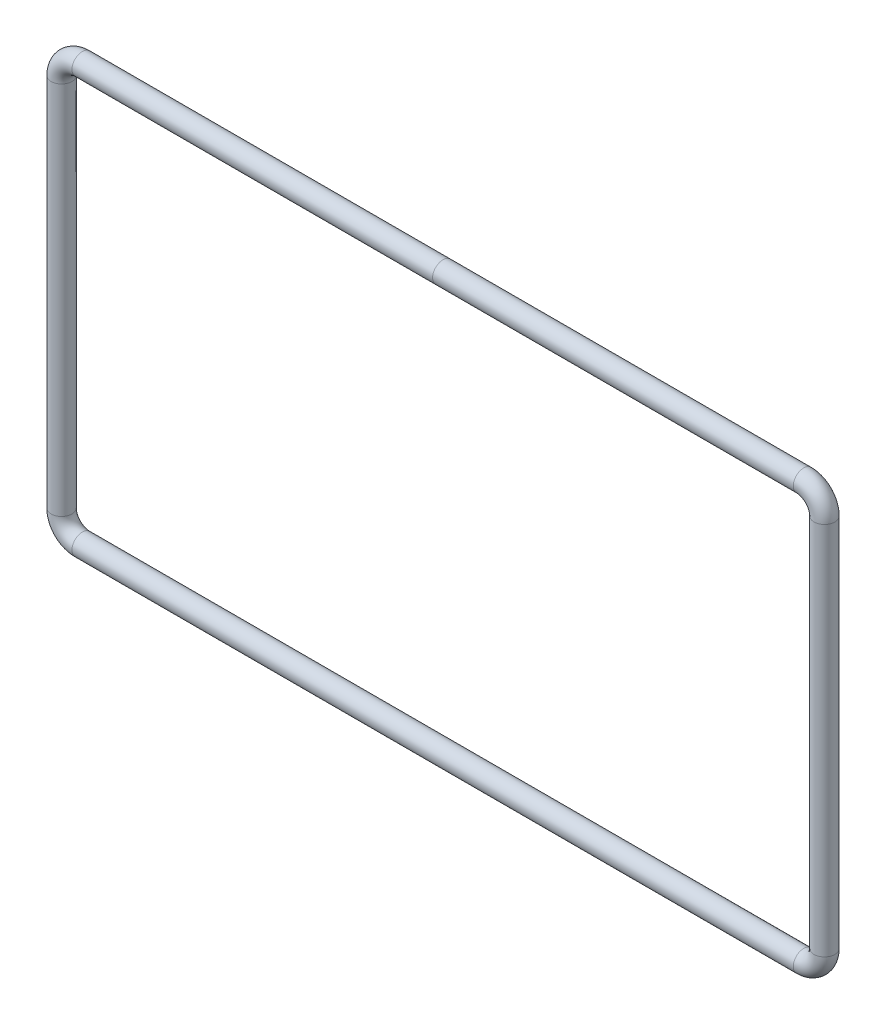
SolidWorks part; units mm, degrees
ref_plane "Plano frontal" through (0, 0, 0) normal (0, 0, 1) x (1, 0, 0)
ref_plane "Plano superior" through (0, 0, 0) normal (0, 1, 0) x (1, 0, 0)
ref_plane "Plano direito" through (0, 0, 0) normal (1, 0, 0) x (0, 0, -1)
sketch "Esboço1" plane through (0, 0, 0) normal (0, 0, 1) x (1, 0, 0)
  line L0 (70, -35) -> (70, 35) construction
  line L1 (-70, -35) -> (70, -35) construction
  line L2 (-70, 35) -> (70, -35) construction
  line L3 (-70, 35) -> (70, 35) construction
  line L4 (-70, -35) -> (-70, 35) construction
  line L5 (-70, -35) -> (70, 35) construction
  line L6 (70, -35) -> (70, 35) construction
  line L7 (-70, -35) -> (70, -35) construction
  line L8 (-70, 35) -> (70, -35) construction
  line L9 (-70, 35) -> (70, 35) construction
  line L10 (-70, -35) -> (-70, 35) construction
  line L11 (-70, -35) -> (70, 35) construction
  line L13 (72.8, -42) -> (-72.8, -42)
  line L14 (77, -37.8) -> (77, 37.8)
  line L15 (72.8, 42) -> (-72.8, 42)
  line L16 (-77, -37.8) -> (-77, 37.8)
  line L17 (77, -42) -> (-77, 42) construction
  line L18 (77, 42) -> (-77, -42) construction
  circle A0 centre (70, -35) radius 5 construction
  circle A1 centre (70, 35) radius 5 construction
  circle A2 centre (-70, 35) radius 5 construction
  circle A3 centre (-70, -35) radius 5 construction
  circle A4 centre (70, -35) radius 5 construction
  circle A5 centre (70, 35) radius 5 construction
  circle A6 centre (-70, 35) radius 5 construction
  circle A7 centre (-70, -35) radius 5 construction
  arc A8 (-72.8, -42) -> (-77, -37.8) centre (-72.8, -37.8) cw
  arc A9 (72.8, -42) -> (77, -37.8) centre (72.8, -37.8) ccw
  arc A10 (72.8, 42) -> (77, 37.8) centre (72.8, 37.8) cw
  arc A11 (-72.8, 42) -> (-77, 37.8) centre (-72.8, 37.8) ccw
  point P20 (0, 0)
  dimension "D1" = 7
  dimension "D3" = 4.2
  dimension "D2" = 7
sketch "Esboço2" plane through (0, 0, 0) normal (1, 0, 0) x (0, 0, -1)
  circle A0 centre (0, 42) radius 2.1
  point P0 (0, 42)
  dimension "D1" = 4.2
sweep "Varredura1" add profiles "Esboço2" path "Esboço1"
